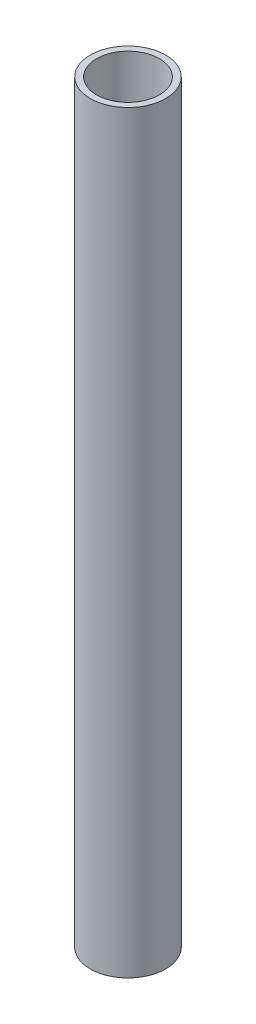
SolidWorks part; units mm, degrees
material "Hexcel AS4C (3000 丝)"
ref_plane "前视基准面" through (0, 0, 0) normal (0, 0, 1) x (1, 0, 0)
ref_plane "上视基准面" through (0, 0, 0) normal (0, 1, 0) x (1, 0, 0)
ref_plane "右视基准面" through (0, 0, 0) normal (1, 0, 0) x (0, 0, -1)
sketch "草图1" plane through (0, 0, 0) normal (0, 1, 0) x (1, 0, 0)
  circle A0 centre (0, 0) radius 6
  circle A1 centre (0, 0) radius 5
  dimension "D1" = 12
  dimension "D2" = 10
extrude "凸台-拉伸1" add sketch "草图1" along normal blind 50
sketch "草图3" plane through (0, 50, 0) normal (0, 1, 0) x (1, 0, 0)
  circle A0 centre (0, 0) radius 5 construction
  circle A1 centre (0, 0) radius 6
  circle A2 centre (0, 0) radius 6
  circle A3 centre (0, 0) radius 5
  dimension "D1" = 0
extrude "凸台-拉伸2" add sketch "草图3" along normal offset from surface (70 mm away) 120 up to face at (0, 0, 6)
